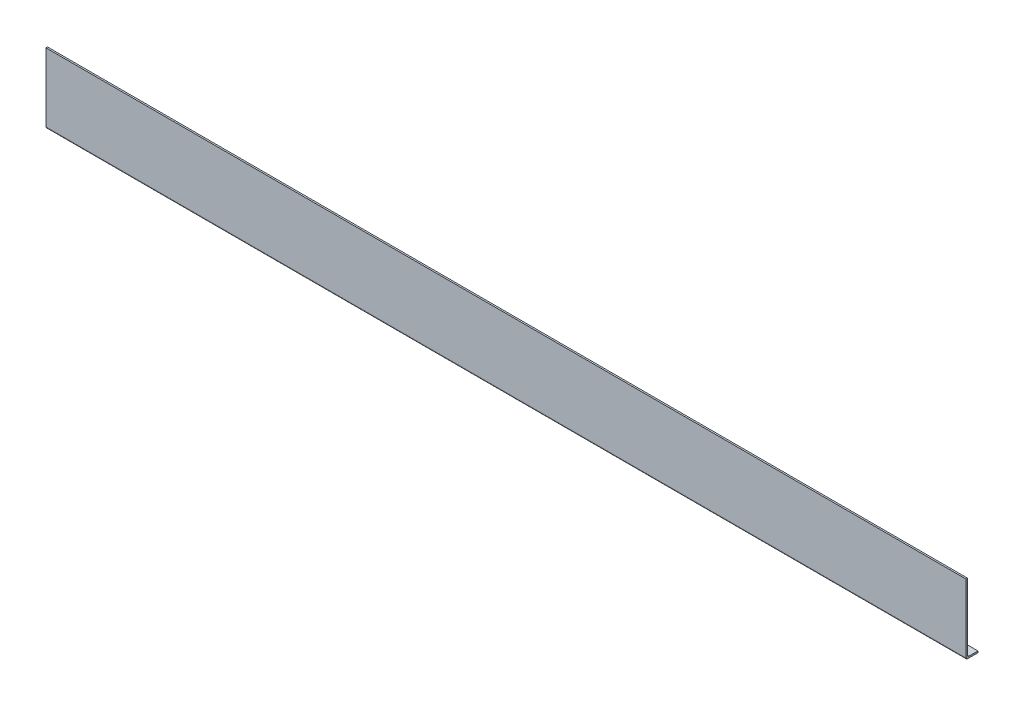
SolidWorks part; units mm, degrees
ref_plane "Front Plane" through (0, 0, 0) normal (0, 0, 1) x (1, 0, 0)
ref_plane "Top Plane" through (0, 0, 0) normal (0, 1, 0) x (1, 0, 0)
ref_plane "Right Plane" through (0, 0, 0) normal (1, 0, 0) x (0, 0, -1)
sketch "Sketch1" plane through (0, 0, 0) normal (1, 0, 0) x (0, 0, -1)
  line L0 (0, 0) -> (-23, 0)
  line L1 (-23, 0) -> (-23, 133)
  line L2 (0, 3) -> (-20, 3)
  line L3 (-20, 3) -> (-20, 133)
  line L4 (-23, 133) -> (-20, 133)
  line L5 (0, 3) -> (0, 0)
  dimension "D1" = 3
  dimension "D2" = 133
  dimension "D3" = 23
extrude "Boss-Extrude1" add sketch "Sketch1" along normal blind 1750
fillet "Fillet1" radius 3 2 edges at (875, 3, 20) (875, 0, 23)
equation "\"totalWidth\"= 1930"
equation "\"D1@Boss-Extrude1\"= \"boxWidth\" - 180"
equation "\"CarBeamWidth\"=700.0"
equation "\"WheelWidth\"=650.0"
equation "\"Wheel_FrontBoxDistance\"=1390.0"
equation "\"boxLength\"=5100.0"
equation "\"boxWidth\"=1930.0"
equation "\"MetalSheet_3mm_length\"=5030.0"
equation "\"MetalSheet_3mm_width\"=1923.0"
equation "\"MetalSheet_3mm_FloorCut_L_length\"=1764.0"
equation "\"MetalSheet_3mm_FloorCut_L_disdance\"=1665.0"
equation "\"MetalSheet_3mm_FloorCut_R_length\"=1764.0"
equation "\"MetalSheet_3mm_FloorCut_R_disdance\"=1665.0"
equation "\"indoorHeight\"=1940.0"
equation "\"indoorHeight_para\"=25.0"
equation "\"rearLightHeight_para\"=265.0"
equation "\"doorColumnBar_A_FR_3mm_length_Cut\"=2310.0"
equation "\"A\"=0.0"
equation "\"haveDoor_R\"=1"
equation "\"side_door_bottom_R_3mm_length\"=1934.0"
equation "\"side_door_bottom_R_3mm_toFrontDistance\"=1583.0"
equation "\"1Bar_Side_RF_3mm_length\"=1493.0"
equation "\"1Bar_Side_RB_3mm_length\"=1493.0"
equation "\"DoorSeparator_RF_3mm_withHinge_toFrontDistance\"=1673.0"
equation "\"DoorSeparator_RF_3mm_withHinge_exist\"=1"
equation "\"DoorSeparator_RB_3mm_withHinge_toFrontDistance\"=3427.0"
equation "\"DoorSeparator_RB_3mm_withHinge_exist\"=1"
equation "\"Door_R1_L_open_Single_toFrontDistance\"=2547.5"
equation "\"Door_R1_L_open_Single_exist\"=1"
equation "\"door_base_long7_R1_L_open_Single_height\"=1890.0"
equation "\"door_base_short7_R1_L_open_Single_height\"=1890.0"
equation "\"door_base_short7_R1_L_open_Single_width\"=864"
equation "\"Door_R1_R_open_Single_toFrontDistance\"=3422.0"
equation "\"Door_R1_R_open_Single_exist\"=1"
equation "\"door_base_long7_R1_R_open_Single_height\"=1890.0"
equation "\"door_base_short7_R1_R_open_Single_height\"=1890.0"
equation "\"door_base_short7_R1_R_open_Single_width\"=864"
equation "\"x\"=66.0"
equation "\"door_base_double_BL_height\"=1890.0"
equation "\"door_base_short7_BL_Single_height\"=1890.0"
equation "\"door_base_short7_BL_Single_width\"=864"
equation "\"door_base_long7_BR_Single_height\"=1890.0"
equation "\"door_base_short7_BR_Single_height\"=1890.0"
equation "\"door_base_short7_BR_Single_width\"=864"
equation "\"da\"=62.0"
equation "\"SquareTube_length\"=1923.0"
equation "\"channelSteel_length\"=5030.0"
equation "\"SquareTube_inFront_AvgDistance\"=285.0"
equation "\"SquareTube_inFront_TotalCount\"=5"
equation "\"SquareTube_inFront1_cutDepth50_R\"=0.5"
equation "\"SquareTube_inFront1_cutDepth50_L\"=0.5"
equation "\"SquareTube_inFront2_cutDepth50_R\"=0.5"
equation "\"SquareTube_inFront2_cutDepth50_L\"=0.5"
equation "\"SquareTube_inFront3_cutDepth50_R\"=0.5"
equation "\"SquareTube_inFront3_cutDepth50_L\"=0.5"
equation "\"SquareTube_inFront4_cutDepth50_R\"=0.5"
equation "\"SquareTube_inFront4_cutDepth50_L\"=0.5"
equation "\"SquareTube_inFront5_cutDepth50_R\"=50"
equation "\"SquareTube_inFront5_cutDepth50_L\"=50"
equation "\"SquareTube_inFront6_cutDepth50_R\"=50"
equation "\"SquareTube_inFront6_cutDepth50_L\"=50"
equation "\"SquareTube_inFront7_cutDepth50_R\"=50"
equation "\"SquareTube_inFront7_cutDepth50_L\"=50"
equation "\"SquareTube_inFront8_cutDepth50_R\"=50"
equation "\"SquareTube_inFront8_cutDepth50_L\"=50"
equation "\"SquareTube_inFront9_cutDepth50_R\"=50"
equation "\"SquareTube_inFront9_cutDepth50_L\"=50"
equation "\"SquareTube_inFront10_cutDepth50_R\"=50"
equation "\"SquareTube_inFront10_cutDepth50_L\"=50"
equation "\"SquareTube_inFront11_cutDepth50_R\"=50"
equation "\"SquareTube_inFront11_cutDepth50_L\"=50"
equation "\"SquareTube_inFront12_cutDepth50_R\"=50"
equation "\"SquareTube_inFront12_cutDepth50_L\"=50"
equation "\"SquareTube_inFront13_cutDepth50_R\"=50"
equation "\"SquareTube_inFront13_cutDepth50_L\"=50"
equation "\"SquareTube_inFront14_cutDepth50_R\"=50"
equation "\"SquareTube_inFront14_cutDepth50_L\"=50"
equation "\"SquareTube_inBack_AvgDistance\"=333.125"
equation "\"SquareTube_inBack_TotalCount\"=9"
equation "\"SquareTube_inBack1_cutDepth50_R\"=50"
equation "\"SquareTube_inBack1_cutDepth50_L\"=50"
equation "\"SquareTube_inBack2_cutDepth50_R\"=50"
equation "\"SquareTube_inBack2_cutDepth50_L\"=50"
equation "\"SquareTube_inBack3_cutDepth50_R\"=50"
equation "\"SquareTube_inBack3_cutDepth50_L\"=50"
equation "\"SquareTube_inBack4_cutDepth50_R\"=50"
equation "\"SquareTube_inBack4_cutDepth50_L\"=50"
equation "\"SquareTube_inBack5_cutDepth50_R\"=50"
equation "\"SquareTube_inBack5_cutDepth50_L\"=50"
equation "\"SquareTube_inBack6_cutDepth50_R\"=0.5"
equation "\"SquareTube_inBack6_cutDepth50_L\"=0.5"
equation "\"SquareTube_inBack7_cutDepth50_R\"=0.5"
equation "\"SquareTube_inBack7_cutDepth50_L\"=0.5"
equation "\"SquareTube_inBack8_cutDepth50_R\"=0.5"
equation "\"SquareTube_inBack8_cutDepth50_L\"=0.5"
